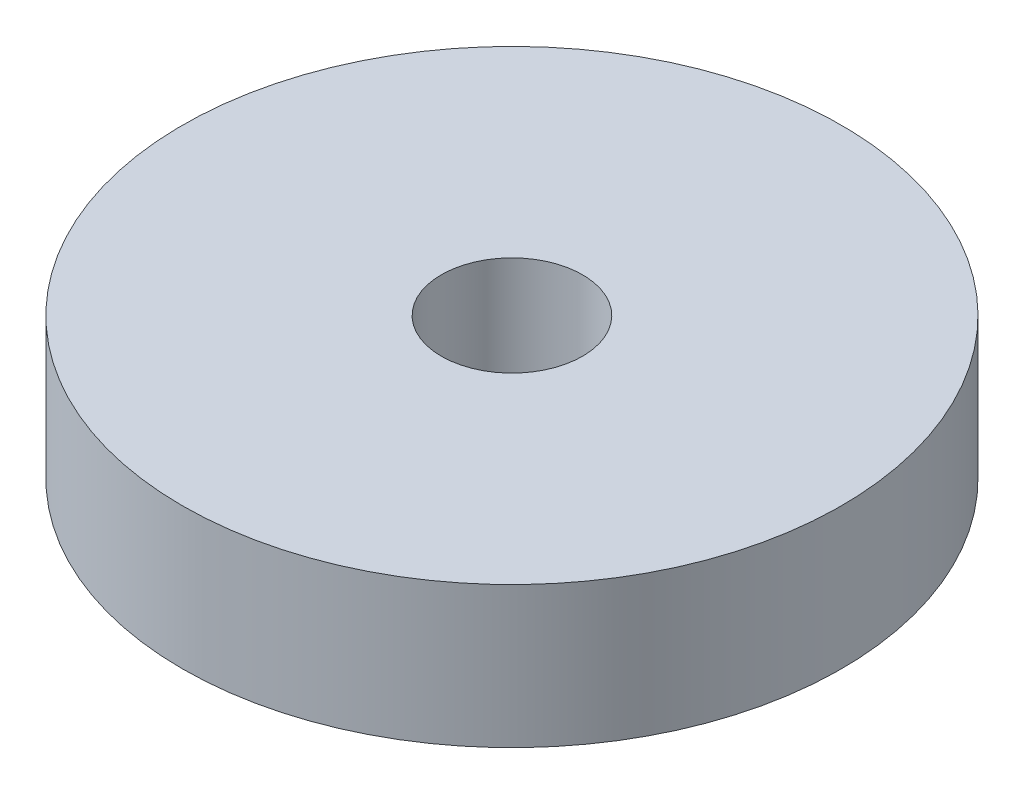
SolidWorks part; units mm, degrees
ref_plane "Front Plane" through (0, 0, 0) normal (0, 0, 1) x (1, 0, 0)
ref_plane "Top Plane" through (0, 0, 0) normal (0, 1, 0) x (1, 0, 0)
ref_plane "Right Plane" through (0, 0, 0) normal (1, 0, 0) x (0, 0, -1)
sketch "Sketch1" plane through (0, 0, 0) normal (0, 1, 0) x (1, 0, 0)
  circle A0 centre (0, 0) radius 7
  circle A1 centre (0, 0) radius 1.5
  dimension "D1" = 14
  dimension "D2" = 3
extrude "Boss-Extrude1" add sketch "Sketch1" along normal blind 3
